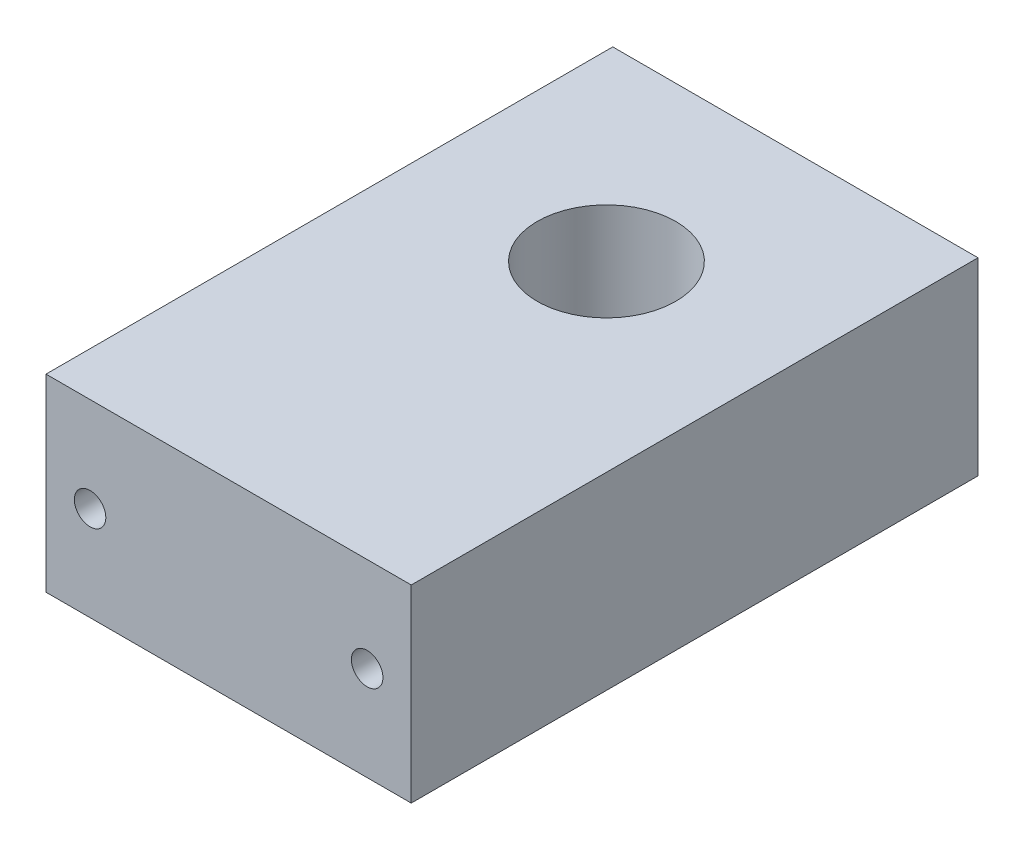
SolidWorks part; units mm, degrees
ref_plane "Front Plane" through (0, 0, 0) normal (0, 0, 1) x (1, 0, 0)
ref_plane "Top Plane" through (0, 0, 0) normal (0, 1, 0) x (1, 0, 0)
ref_plane "Right Plane" through (0, 0, 0) normal (1, 0, 0) x (0, 0, -1)
sketch "Sketch1" plane through (0, 2.5187, -14.699) normal (0, 0, 1) x (1, 0, 0)
  line L0 (-43.1266, 671.9676) -> (-14.1266, 671.9676)
  line L2 (-14.1266, 671.9676) -> (14.8734, 671.9676)
  line L3 (14.8734, 671.9676) -> (14.8734, 701.9676)
  line L4 (14.8734, 701.9676) -> (-43.1266, 701.9676)
  line L5 (-43.1266, 701.9676) -> (-43.1266, 671.9676)
  line L8 (-14.1266, 123.5532) -> (-14.1266, 923.5532) construction
  dimension "D1" = 58
  dimension "D2" = 30
extrude "Boss-Extrude1" add sketch "Sketch1" along normal up to surface (90 mm away)
sketch "Sketch3" plane through (0, 674.4863, 0) normal (0, -1, 0) x (1, 0, 0)
  circle A0 centre (-14.1266, 15.301) radius 11
  point P0 (-14.1266, 15.301)
  dimension "D1" = 22
extrude "Cut-Extrude1" cut sketch "Sketch3" against normal through all
hole_wizard "M6 Tapped Hole" positions "Sketch6" profile "Sketch7" tap size "M6" standard "ISO" end condition through all
sketch "Sketch6" plane through (545.7192, 1586.9579, 85.301) normal (0, 0, 1) x (-1, 0, 0)
  point P0 (514.8458, 897.4716)
  point P3 (537.8458, 897.4716)
  point P6 (581.8458, 897.4716)
  point P9 (604.8458, 897.4716)
  point P12 (514.8458, 1450.8861)
  point P15 (514.8458, 1412.8861)
  point P18 (537.8458, 1453.8861)
  point P21 (537.8458, 1409.8861)
  point P24 (581.8458, 1453.8861)
  point P27 (581.8458, 1409.8861)
  point P30 (604.8458, 1450.8861)
  point P33 (604.8458, 1412.8861)
  point P36 (514.8458, 1431.8861)
  point P39 (537.8458, 1431.8861)
  point P43 (581.8458, 1431.8861)
  point P46 (604.8458, 1431.8861)
sketch "Sketch7" plane through (30.8734, 689.4863, 85.301) normal (1, 0, 0) x (0, -1, 0)
  line L0 (0, 0) -> (0, 100)
  line L1 (0, 100) -> (2.5, 100)
  line L2 (2.5, 100) -> (2.5, 0)
  line L3 (2.5, 0) -> (0, 0)
  line L4 (0, -6.35) -> (0, 107.95) construction
  dimension "Thread Major Dia." = 5
  dimension "Thru Tap Drill Depth" = 100
